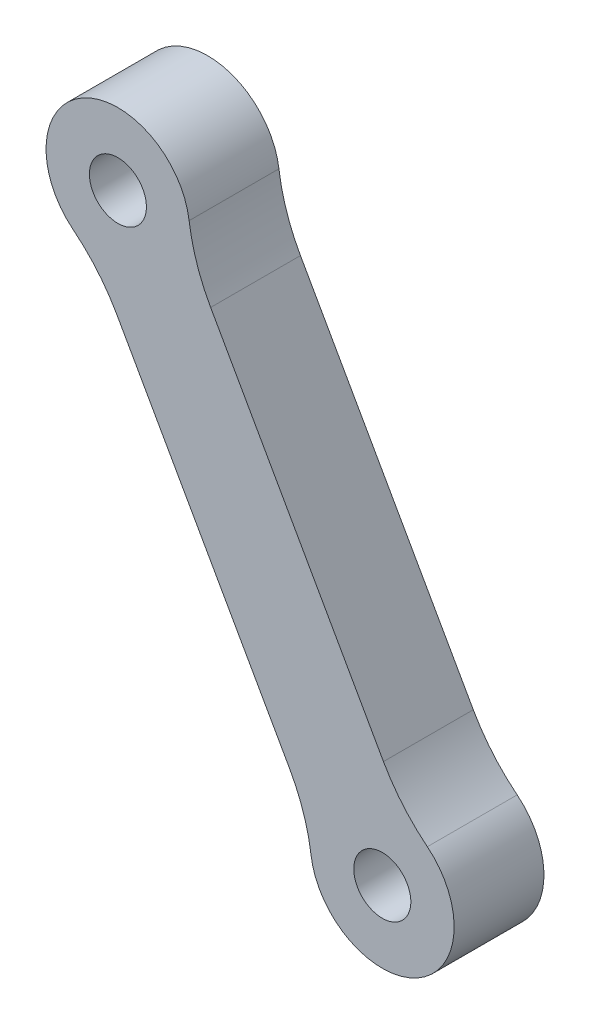
SolidWorks part; units mm, degrees
ref_plane "Front Plane" through (0, 0, 0) normal (0, 0, 1) x (1, 0, 0)
ref_plane "Top Plane" through (0, 0, 0) normal (0, 1, 0) x (1, 0, 0)
ref_plane "Right Plane" through (0, 0, 0) normal (1, 0, 0) x (0, 0, -1)
ref_plane "Plane1" through (0, 0, 63) normal (0, 0, 1) x (1, 0, 0)
sketch "Sketch1" plane through (0, 0, 63) normal (0, 0, 1) x (1, 0, 0)
  line L0 (8.1819, -16.6057) -> (17.8022, -33.6912)
  line L1 (23.0304, -30.7474) -> (13.4101, -13.6619)
  arc A0 (17.8022, -33.6912) -> (19.0008, -37.2757) centre (9.0885, -38.5975) cw
  arc A1 (19.0008, -37.2757) -> (25.4738, -33.631) centre (22.9657, -36.747) ccw
  arc A2 (25.4738, -33.631) -> (23.0304, -30.7474) centre (31.744, -25.841) cw
  arc A3 (13.4101, -13.6619) -> (12.2115, -10.0773) centre (22.1238, -8.7555) cw
  arc A4 (12.2115, -10.0773) -> (5.7385, -13.7221) centre (8.2466, -10.6061) ccw
  arc A5 (5.7385, -13.7221) -> (8.1819, -16.6057) centre (-0.5317, -21.5121) cw
  circle A6 centre (8.2466, -10.6061) radius 2
  circle A7 centre (22.9657, -36.747) radius 2
extrude "Boss-Extrude1" add sketch "Sketch1" against normal blind 5
sketch "Sketch2" plane through (0, 0, 58) normal (0, 0, -1) x (-1, 0, 0)
  circle A0 centre (-22.9657, -36.747) radius 2
  circle A1 centre (-22.9657, -36.747) radius 1.5875
extrude "Boss-Extrude2" add sketch "Sketch2" against normal through all
sketch "Sketch3" plane through (0, 0, 58) normal (0, 0, -1) x (-1, 0, 0)
  circle A0 centre (-8.2466, -10.6061) radius 2
  circle A1 centre (-8.2466, -10.6061) radius 1.5875
extrude "Boss-Extrude3" add sketch "Sketch3" against normal through all
